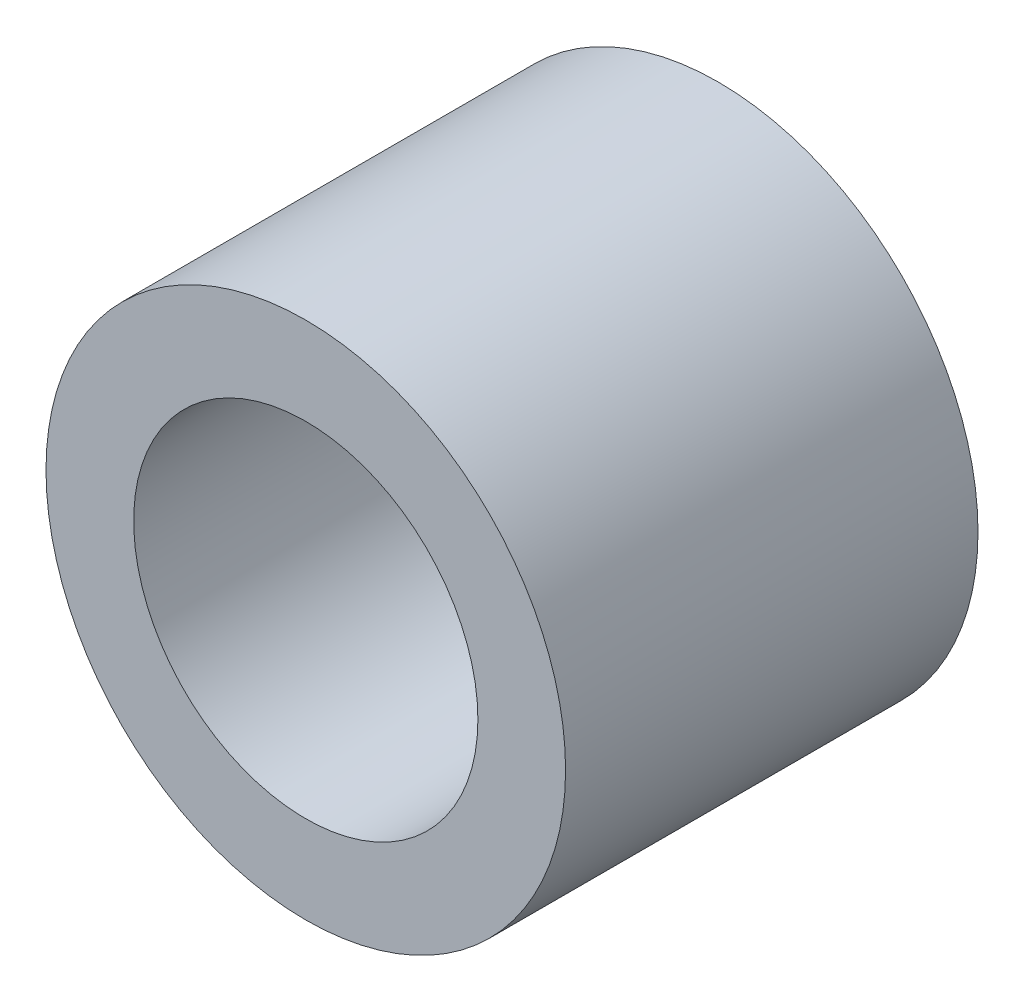
SolidWorks part; units mm, degrees
material "6061-T6 (SS)"
ref_plane "Front Plane" through (0, 0, 0) normal (0, 0, 1) x (1, 0, 0)
ref_plane "Top Plane" through (0, 0, 0) normal (0, 1, 0) x (1, 0, 0)
ref_plane "Right Plane" through (0, 0, 0) normal (1, 0, 0) x (0, 0, -1)
sketch "Sketch1" plane through (0, 0, 0) normal (0, 0, 1) x (1, 0, 0)
  circle A0 centre (0, 0) radius 2.65
  circle A1 centre (0, 0) radius 4
  dimension "D1" = 8
  dimension "D2" = 5.3
extrude "Boss-Extrude1" add sketch "Sketch1" along normal blind 6.35
